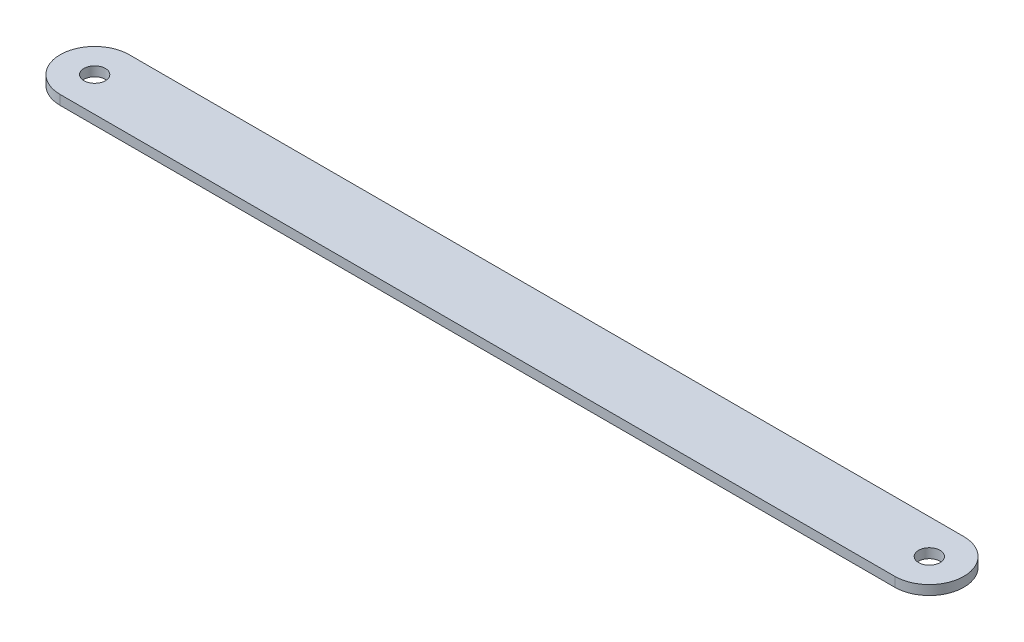
SolidWorks part; units mm, degrees
ref_plane "Front Plane" through (0, 0, 0) normal (0, 0, 1) x (1, 0, 0)
ref_plane "Top Plane" through (0, 0, 0) normal (0, 1, 0) x (1, 0, 0)
ref_plane "Right Plane" through (0, 0, 0) normal (1, 0, 0) x (0, 0, -1)
sketch "Sketch1" plane through (0, 0, 0) normal (0, 1, 0) x (1, 0, 0)
  line L0 (-270, 0) -> (0, 0) construction
  line L1 (-270, -14.5) -> (0, -14.5)
  line L2 (0, 340) -> (0, -14.5)
  line L3 (0, 5.5) -> (-159.9638, 5.5) construction
  line L4 (-159.9638, 5.5) -> (-159.9638, 310) construction
  line L5 (-159.9638, 310) -> (0.0362, 310) construction
  line L6 (-175.5, 384.5) -> (51.2761, 384.5) construction
  line L7 (-175.4638, 340) -> (0, 340)
  line L8 (-189.9638, 325.5) -> (-189.9638, 225.6066)
  line L9 (-229.9638, 14.5) -> (-270, 14.5)
  line L10 (-189.9638, 195.6066) -> (-189.9638, 54.5)
  line L11 (-189.9638, 54.5) -> (-229.9638, 14.5)
  circle A0 centre (-270, 0) radius 4.5
  arc A1 (-270, -14.5) -> (-270, 14.5) centre (-270, 0) cw
  circle A2 centre (-175.4638, 325.5) radius 4.5
  arc A3 (-175.4638, 340) -> (-189.9638, 325.5) centre (-175.4638, 325.5) ccw
  circle A4 centre (-189.9638, 210.6066) radius 6.5
  circle A5 centre (-180.2138, 210.6066) radius 1.75
  circle A6 centre (-189.9638, 220.4066) radius 1.75
  circle A7 centre (-189.9638, 200.8066) radius 1.75
  circle A8 centre (-199.7138, 210.6066) radius 1.75
  arc A9 (-189.9638, 195.6066) -> (-189.9638, 225.6066) centre (-189.9638, 210.6066) cw
  point P18 (-189.9638, 14.5)
  dimension "D2" = 9
  dimension "D3" = 9
  dimension "D7" = 10
  dimension "D10" = 10
  dimension "D13" = 13
  dimension "D14" = 3.5
  dimension "D19" = 15
  dimension "D1" = 270
  dimension "D4" = 160
  dimension "D5" = 304.5
  dimension "D6" = 20
  dimension "D8" = 30
  dimension "D9" = 30
  dimension "D11" = 44.5
  dimension "D12" = 311
  dimension "D15" = 19.5
  dimension "D16" = 9.75
  dimension "D17" = 9.8
  dimension "D18" = 9.8
extrude "Boss-Extrude1" add sketch "Sketch1" along normal blind 4
mirror "Mirror1" about plane through (0, 4, -340) normal (-1, 0, 0) of "Boss-Extrude1"
sketch "Sketch2" plane through (0, 4, 0) normal (0, 1, 0) x (1, 0, 0)
  line L0 (-270, -14.5) -> (270, -14.5) construction
  circle A0 centre (0, 305.5) radius 2
  point P4 (0, -14.5)
  dimension "D1" = 4
  dimension "D2" = 320
extrude "Cut-Extrude1" cut sketch "Sketch2" against normal blind 4
sketch "Sketch3" plane through (0, 4, 0) normal (0, 1, 0) x (1, 0, 0)
  line L0 (-270, -14.5) -> (270, -14.5) construction
  circle A0 centre (-170, 15.5) radius 2
  circle A1 centre (170, 15.5) radius 2
  point P6 (0, -14.5)
  dimension "D1" = 4
  dimension "D2" = 4
  dimension "D3" = 170
  dimension "D4" = 170
  dimension "D5" = 30
  dimension "D6" = 30
extrude "Cut-Extrude2" cut sketch "Sketch3" against normal blind 10
sketch "Sketch4" plane through (0, 4, 0) normal (0, 1, 0) x (1, 0, 0)
  line L0 (-175.4638, 311) -> (175.4638, 311)
  line L1 (189.9638, 325.5) -> (382.2576, 325.5)
  line L2 (382.2576, 325.5) -> (382.2576, -89.2162)
  line L3 (382.2576, -89.2162) -> (-350.5019, -89.2162)
  line L4 (-350.5019, -89.2162) -> (-350.5019, 325.5)
  line L5 (-350.5019, 325.5) -> (-189.9638, 325.5)
  arc A0 (-189.9638, 325.5) -> (-175.4638, 311) centre (-175.4638, 325.5) ccw
  arc A1 (175.4638, 311) -> (189.9638, 325.5) centre (175.4638, 325.5) ccw
extrude "Cut-Extrude3" cut sketch "Sketch4" against normal blind 10
